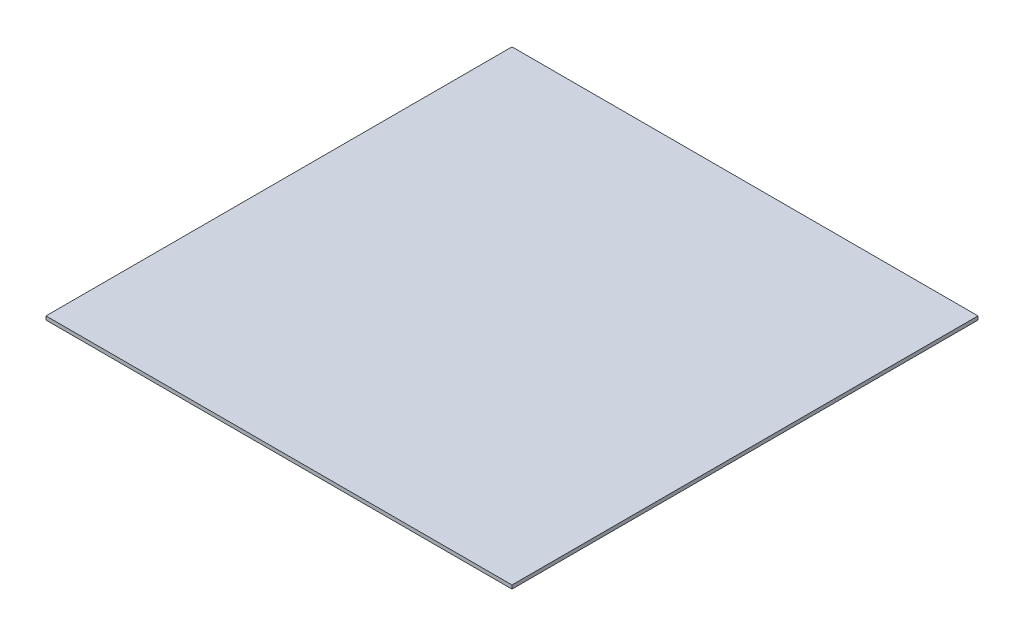
SolidWorks part; units mm, degrees
ref_plane "Front Plane" through (0, 0, 0) normal (0, 0, 1) x (1, 0, 0)
ref_plane "Top Plane" through (0, 0, 0) normal (0, 1, 0) x (1, 0, 0)
ref_plane "Right Plane" through (0, 0, 0) normal (1, 0, 0) x (0, 0, -1)
sketch "Sketch1" plane through (0, 0, 0) normal (0, 1, 0) x (1, 0, 0)
  line L0 (0, -55) -> (0, 55) construction
  line L1 (-101.6, 101.6) -> (101.6, 101.6)
  line L2 (-101.6, 101.6) -> (-101.6, -101.6)
  line L3 (-101.6, -101.6) -> (101.6, -101.6)
  line L4 (101.6, 101.6) -> (101.6, -101.6)
  line L5 (-55, 0) -> (55, 0) construction
  point P4 (0, 101.6)
  point P7 (-101.6, 0)
  dimension "D1" = 203.2
  dimension "D2" = 203.2
extrude "Boss-Extrude1" add sketch "Sketch1" along normal blind 1.5875
